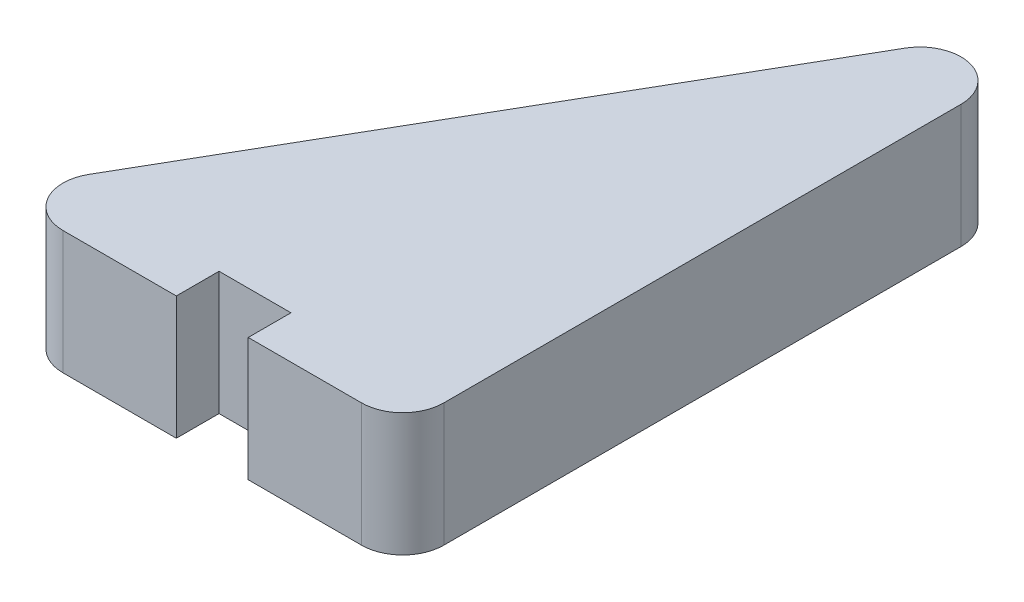
SolidWorks part; units mm, degrees
material "Pine"
ref_plane "Front Plane" through (0, 0, 0) normal (0, 0, 1) x (1, 0, 0)
ref_plane "Top Plane" through (0, 0, 0) normal (0, 1, 0) x (1, 0, 0)
ref_plane "Right Plane" through (0, 0, 0) normal (1, 0, 0) x (0, 0, -1)
sketch "Sketch1" plane through (0, 0, 0) normal (0, 1, 0) x (1, 0, 0)
  line L10 (0, 6.35) -> (0, 86.2867)
  line L11 (-11.8493, 89.4617) -> (-58.0007, 9.525)
  line L12 (-52.5015, 0) -> (-6.35, 0)
  arc A6 (-58.0007, 9.525) -> (-52.5015, 0) centre (-52.5015, 6.35) ccw
  arc A7 (0, 6.35) -> (-6.35, 0) centre (-6.35, 6.35) cw
  arc A8 (0, 86.2867) -> (-11.8493, 89.4617) centre (-6.35, 86.2867) ccw
  point P3 (-63.5, 0)
  point P4 (0, 0)
  point P7 (0, 0)
  point P10 (0, 0)
  point P13 (0, 109.9852)
  dimension "D2" = 6.35
  dimension "D1" = 63.5
  dimension "D3" = 60
extrude "Boss-Extrude1" add sketch "Sketch1" along normal blind 19.05
sketch "Sketch2" plane through (0, 19.05, 0) normal (0, 1, 0) x (1, 0, 0)
  line L0 (-52.5015, 0) -> (-6.35, 0) construction
  line L1 (-34.982, 0) -> (-23.8695, 0)
  line L2 (-34.982, 0) -> (-34.982, 6.604)
  line L3 (-34.982, 6.604) -> (-23.8695, 6.604)
  line L4 (-23.8695, 0) -> (-23.8695, 6.604)
  line L7 (0, 6.35) -> (0, 86.2867) construction
  dimension "D1" = 11.1125
  dimension "D2" = 6.604
  dimension "D3" = 23.8695
extrude "Cut-Extrude1" cut sketch "Sketch2" against normal through all
